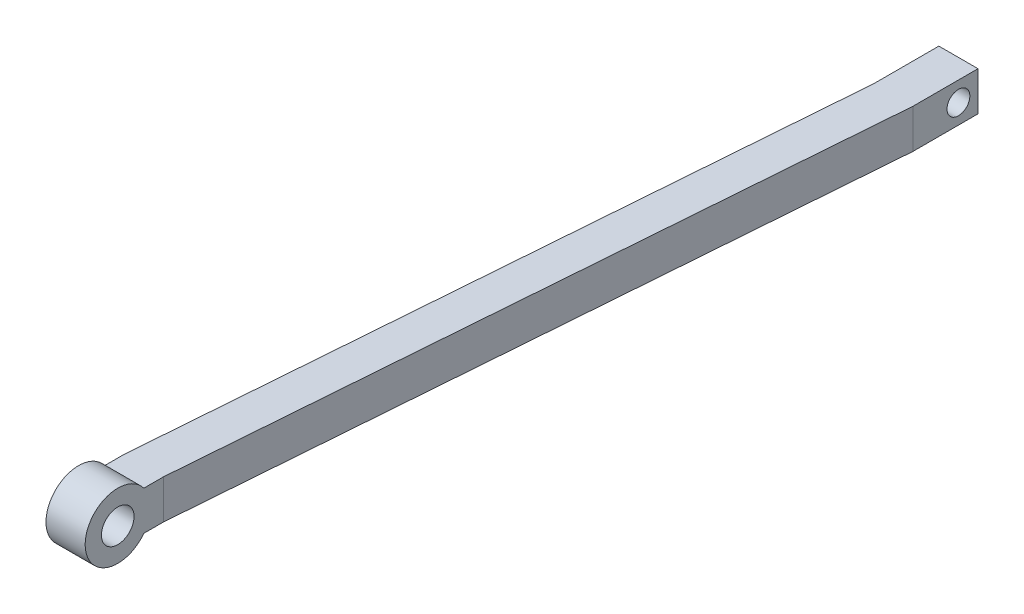
SolidWorks part; units mm, degrees
ref_plane "Front Plane" through (0, 0, 0) normal (0, 0, 1) x (1, 0, 0)
ref_plane "Top Plane" through (0, 0, 0) normal (0, 1, 0) x (1, 0, 0)
ref_plane "Right Plane" through (0, 0, 0) normal (1, 0, 0) x (0, 0, -1)
sketch "Sketch1" plane through (0, 0, 0) normal (0, 1, 0) x (1, 0, 0)
  line L0 (20, 241.29) -> (20, 117.7717) construction
  line L1 (-3.5, 0) -> (-3.5, 94.7505) construction
  line L2 (16.5, 244.79) -> (-3.5, 244.79) construction
  line L3 (22.5, 241.29) -> (22.5, 260.4188)
  line L4 (16.5, 247.29) -> (22.5, 247.29)
  line L5 (-6, 0) -> (-6, -20.3088)
  line L6 (0, -6) -> (-6, -6)
  line L7 (6, 14) -> (22.5, 227.29)
  line L8 (-6, -6) -> (22.5, -6)
  line L9 (-6, -6) -> (-6, 247.29)
  line L10 (-6, 247.29) -> (22.5, 247.29)
  line L11 (22.5, -6) -> (22.5, 247.29)
  line L12 (10.5, 247.29) -> (22.5, 247.29)
  line L13 (10.5, 247.29) -> (10.5, 227.29)
  line L14 (10.5, 227.29) -> (22.5, 227.29)
  line L15 (22.5, 247.29) -> (22.5, 227.29)
  line L16 (6, -6) -> (-6, -6)
  line L17 (6, -6) -> (6, 14)
  line L18 (6, 14) -> (-6, 14)
  line L19 (-6, -6) -> (-6, 14)
  line L20 (10.5, 227.29) -> (-6, 14)
  circle A0 centre (0, 0) radius 3.5 construction
  circle A1 centre (16.5, 241.29) radius 3.5 construction
  circle A2 centre (16.5, 241.29) radius 6 construction
  circle A3 centre (0, 0) radius 6 construction
  point P26 (10.5, 241.29)
  point P30 (6, 0)
  dimension "D1" = 7
  dimension "D2" = 7
  dimension "D4" = 12
  dimension "D5" = 12
  dimension "D3" = 20
  dimension "D6" = 241.29
  dimension "D7" = 20
  dimension "D8" = 20
extrude "Boss-Extrude1" add sketch "Sketch1" against normal blind 12 contours L14 L20 L18 L7 | L13 L14 L11 L3 L4 L10 | L17 L18 L9 L5 L6 L8
sketch "Sketch2" plane through (-6, 0, 0) normal (-1, 0, 0) x (0, 0, 1)
  line L0 (6, -12) -> (6, 0) construction
  line L1 (6, -12) -> (-14, -12) construction
  circle A0 centre (0, -6) radius 6
  circle A1 centre (0, -6) radius 5
  dimension "D1" = 12
  dimension "D2" = 10
extrude "Cut-Extrude3" cut sketch "Sketch2" against normal up to next contours A1
sketch "Sketch3" plane through (22.5, 0, 0) normal (1, 0, 0) x (0, 0, -1)
  line L0 (227.29, 0) -> (247.29, 0) construction
  line L1 (247.29, -12) -> (247.29, 0) construction
  circle A0 centre (241.29, -6) radius 6
  circle A1 centre (241.29, -6) radius 3.5
  dimension "D1" = 12
  dimension "D2" = 7
extrude "Cut-Extrude4" cut sketch "Sketch3" against normal up to next contours A1
sketch "Sketch4" plane through (-6, 0, 0) normal (-1, 0, 0) x (0, 0, 1)
  circle A0 centre (0, -6) radius 10
  circle A1 centre (0, -6) radius 5 construction
  circle A2 centre (0, -6) radius 5
  dimension "D1" = 20
extrude "Boss-Extrude2" add sketch "Sketch4" against normal up to surface (12 mm away) up to face at (6, -6, -5)
